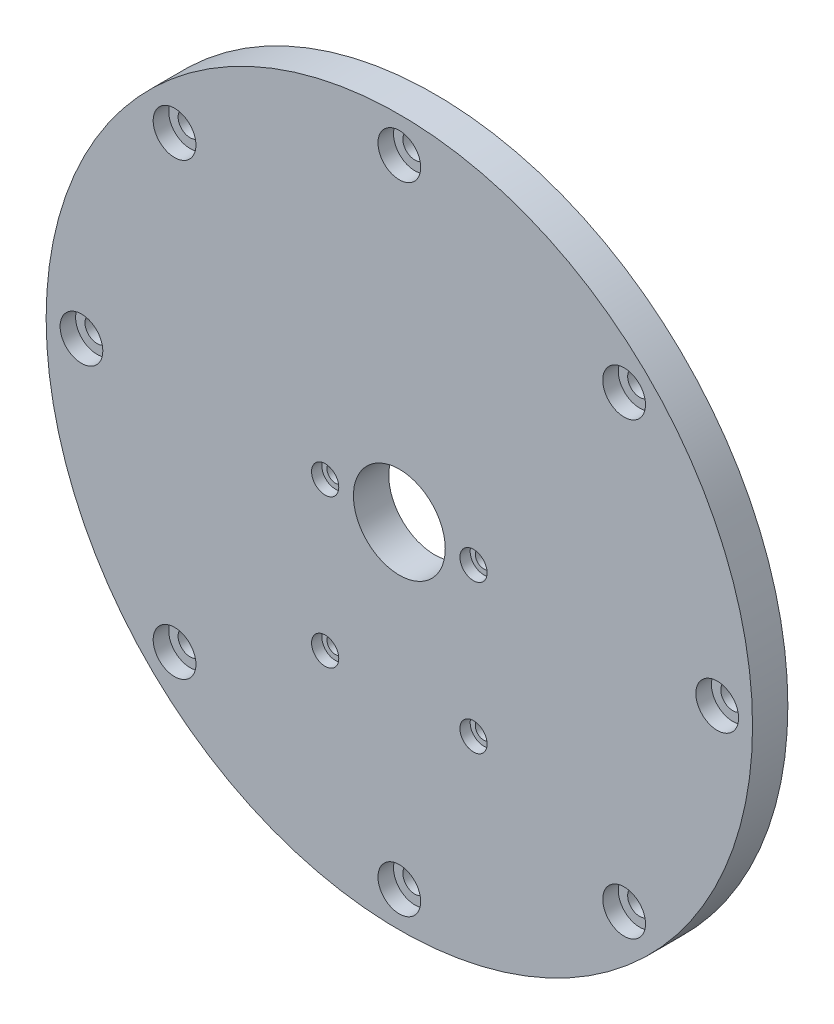
SolidWorks part; units mm, degrees
ref_plane "正面" through (0, 0, 0) normal (0, 0, 1) x (1, 0, 0)
ref_plane "平面" through (0, 0, 0) normal (0, 1, 0) x (1, 0, 0)
ref_plane "右側面" through (0, 0, 0) normal (1, 0, 0) x (0, 0, -1)
sketch "ｽｹｯﾁ1" plane through (0, 0, 0) normal (0, 0, 1) x (1, 0, 0)
  circle A0 centre (0, 0) radius 50
  dimension "D1" = 100
extrude "ﾎﾞｽ - 押し出し1" add sketch "ｽｹｯﾁ1" along normal blind 5
hole_wizard "M2 丸平ねじ用座ぐり穴1" positions "ｽｹｯﾁ2" profile "ｽｹｯﾁ3" counterbore size "M2" standard "JIS" end condition through all
sketch "ｽｹｯﾁ2" plane through (0, 0, 5) normal (0, 0, 1) x (1, 0, 0)
  point P0 (-10.5, 0)
  point P4 (-10.5, -21)
  dimension "D1" = 10.5
  dimension "D2" = 10.5
  dimension "D3" = 21
sketch "ｽｹｯﾁ3" plane through (-10.5, 0, 5) normal (1, 0, 0) x (0, -1, 0)
  line L0 (0, 0) -> (0, 5)
  line L1 (0, 5) -> (1.2, 5)
  line L3 (1.2, 5) -> (1.2, 1.45)
  line L4 (1.2, 1.45) -> (1.925, 1.45)
  line L5 (1.925, 1.45) -> (1.925, 0)
  line L7 (1.925, 0) -> (0, 0)
  line L11 (0, -6.35) -> (0, 107.95) construction
  dimension "通し穴の直径" = 2.4
  dimension "通し穴の深さ" = 5
  dimension "座ぐり穴の直径" = 3.85
  dimension "座ぐり穴の深さ" = 1.45
mirror "ﾐﾗｰ1" about plane through (0, 0, 0) normal (1, 0, 0) of "M2 丸平ねじ用座ぐり穴1"
hole_wizard "M3 丸平ねじ用座ぐり穴2" positions "ｽｹｯﾁ4" profile "ｽｹｯﾁ5" counterbore size "M3" standard "JIS" end condition through all
sketch "ｽｹｯﾁ4" plane through (0, 0, 5) normal (0, 0, 1) x (1, 0, 0)
  point P0 (45, 0)
  point P2 (45, 0)
  dimension "D1" = 45
sketch "ｽｹｯﾁ5" plane through (45, 0, 5) normal (1, 0, 0) x (0, -1, 0)
  line L0 (0, 0) -> (0, 5)
  line L1 (0, 5) -> (1.7, 5)
  line L3 (1.7, 5) -> (1.7, 2.2)
  line L4 (1.7, 2.2) -> (3.025, 2.2)
  line L5 (3.025, 2.2) -> (3.025, 0)
  line L7 (3.025, 0) -> (0, 0)
  line L11 (0, -6.35) -> (0, 107.95) construction
  dimension "通し穴の直径" = 3.4
  dimension "通し穴の深さ" = 5
  dimension "座ぐり穴の直径" = 6.05
  dimension "座ぐり穴の深さ" = 2.2
pattern_circular "円形ﾊﾟﾀｰﾝ1" count 8 every 45 about axis through (0, 0, 0) along (0, 0, 1) of "M3 丸平ねじ用座ぐり穴2"
sketch "ｽｹｯﾁ6" plane through (0, 0, 5) normal (0, 0, 1) x (1, 0, 0)
  circle A0 centre (0, 0) radius 6.5
  dimension "D1" = 13
extrude "ｶｯﾄ - 押し出し1" cut sketch "ｽｹｯﾁ6" against normal through all
